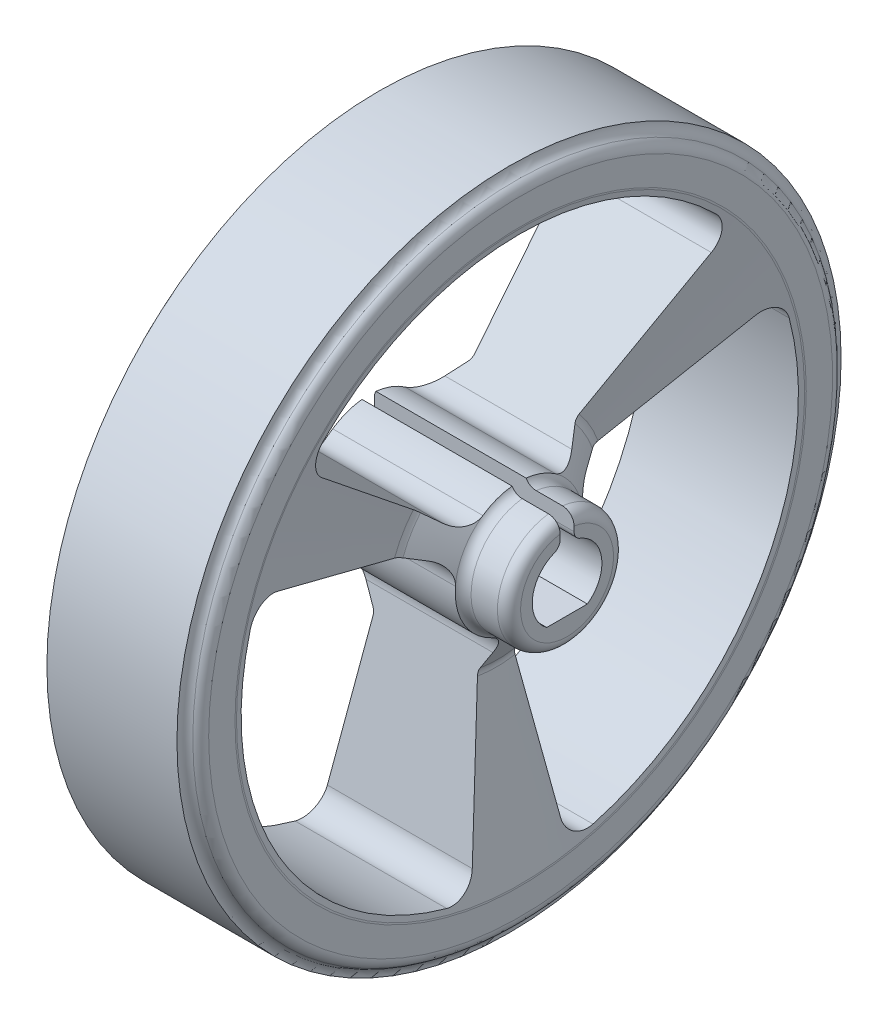
SolidWorks part; units mm, degrees
material "PBT General Purpose"
ref_plane "Front" through (0, 0, 0) normal (0, 0, 1) x (1, 0, 0)
ref_plane "Top" through (0, 0, 0) normal (0, 1, 0) x (1, 0, 0)
ref_plane "Right" through (0, 0, 0) normal (1, 0, 0) x (0, 0, -1)
sketch "Sketch1" plane through (0, 0, 0) normal (0, 1, 0) x (1, 0, 0)
  line L0 (0, 0) -> (14.3, 0) construction
  line L1 (0, 0) -> (0, 2.5)
  line L2 (0.067, 2.75) -> (0.9877, 4.3447)
  line L3 (0, 12.3) -> (0, 13.434)
  line L4 (0.5, 14.3) -> (6.1, 14.3)
  line L5 (3.3, 14.3) -> (3.3, 0) construction
  line L6 (1.05, 4.6632) -> (0.0047, 12.2316)
  line L7 (5.55, 4.6632) -> (6.5953, 12.2316)
  line L8 (6.6, 12.3) -> (6.6, 13.434)
  line L9 (6.533, 2.75) -> (5.6123, 4.3447)
  line L10 (6.966, 2.5) -> (8.1, 2.5)
  line L11 (8.6, 2) -> (8.6, 0)
  line L12 (0, 0) -> (8.6, 0)
  arc A0 (0, 2.5) -> (0.067, 2.75) centre (0.5, 2.5) cw
  arc A1 (0.9877, 4.3447) -> (1.05, 4.6632) centre (0.5547, 4.5947) ccw
  arc A2 (0.0047, 12.2316) -> (0, 12.3) centre (0.5, 12.3) cw
  arc A3 (0, 13.434) -> (0.25, 13.867) centre (0.5, 13.434) cw
  arc A4 (0.25, 13.867) -> (0.5, 14.3) centre (0, 14.3) ccw
  arc A5 (6.35, 13.867) -> (6.1, 14.3) centre (6.6, 14.3) cw
  arc A6 (6.6, 13.434) -> (6.35, 13.867) centre (6.1, 13.434) ccw
  arc A7 (6.5953, 12.2316) -> (6.6, 12.3) centre (6.1, 12.3) ccw
  arc A8 (5.6123, 4.3447) -> (5.55, 4.6632) centre (6.0453, 4.5947) cw
  arc A9 (6.533, 2.75) -> (6.966, 2.5) centre (6.966, 3) ccw
  arc A10 (8.1, 2.5) -> (8.6, 2) centre (8.1, 2) cw
  dimension "D1" = 28.6
  dimension "D2" = 0.5
  dimension "D3" = 6.6
  dimension "D4" = 5
  dimension "D5" = 4.5
  dimension "D6" = 2
  dimension "D7" = 30
  dimension "D8" = 8.6
revolve "Revolve1" add sketch "Sketch1" angle 360 about L12
sketch "Sketch2" plane through (0, 0, 0) normal (1, 0, 0) x (0, 0, -1)
  line L0 (0, 0) -> (0, 12) construction
  line L1 (8.3916, 7.0414) -> (2.7686, 2.3232)
  line L2 (0, 0) -> (10.3923, 6) construction
  line L3 (0, 0) -> (10.3923, -6) construction
  line L4 (0, 0) -> (0, -12) construction
  line L5 (0, 0) -> (-10.3923, -6) construction
  line L6 (0, 0) -> (-10.3923, 6) construction
  line L7 (-8.3916, 7.0414) -> (-2.7686, 2.3232)
  arc A0 (-2.7686, 2.3232) -> (-1.559, 2.2654) centre (-2.1259, 3.0892) ccw
  arc A1 (-8.4532, 8.5172) -> (8.4532, 8.5172) centre (0, 0) cw
  arc A2 (8.4532, 8.5172) -> (8.3916, 7.0414) centre (7.7488, 7.8074) cw
  arc A3 (-8.4532, 8.5172) -> (-8.3916, 7.0414) centre (-7.7488, 7.8074) ccw
  arc A4 (2.7686, 2.3232) -> (1.559, 2.2654) centre (2.1259, 3.0892) cw
  arc A5 (1.559, 2.2654) -> (-1.559, 2.2654) centre (0, 0) ccw
  circle A6 centre (0, 0) radius 2.75 construction
  point P19 (0, 0)
  dimension "D1" = 12
  dimension "D2" = 6
  dimension "D4" = 1
  dimension "D3" = 50
extrude "Cut-Extrude2" cut sketch "Sketch2" against normal through all and the other way through all
pattern_circular "CirPattern1" count 3 over 360 about axis through (0, 0, 0) along (1, 0, 0) of "Cut-Extrude2"
sketch "Sketch3" plane through (0, 0, 0) normal (-1, 0, 0) x (0, 0, 1)
  line L0 (0.875, -1.2183) -> (-0.875, -1.2183)
  line L1 (0.3, 1.7664) -> (0.3, 2.7336)
  line L2 (0, 0) -> (0, 2.75) construction
  line L3 (-0.3, 1.7664) -> (-0.3, 2.7336)
  arc A0 (0.875, -1.2183) -> (0.5526, 1.3945) centre (0, 0) ccw
  arc A1 (0.5526, 1.3945) -> (0.3, 1.7664) centre (0.7, 1.7664) cw
  arc A2 (1.559, 2.2654) -> (-1.559, 2.2654) centre (0, 0) ccw construction
  arc A3 (0.3, 2.7336) -> (-0.3, 2.7336) centre (0, 0) ccw
  arc A4 (-0.875, -1.2183) -> (-0.5526, 1.3945) centre (0, 0) cw
  arc A5 (-0.5526, 1.3945) -> (-0.3, 1.7664) centre (-0.7, 1.7664) ccw
  point P12 (0, -1.2183)
  dimension "D1" = 1.5
  dimension "D3" = 0.4
  dimension "D2" = 0.6
  dimension "D4" = 1.75
extrude "Cut-Extrude3" cut sketch "Sketch3" against normal through all
